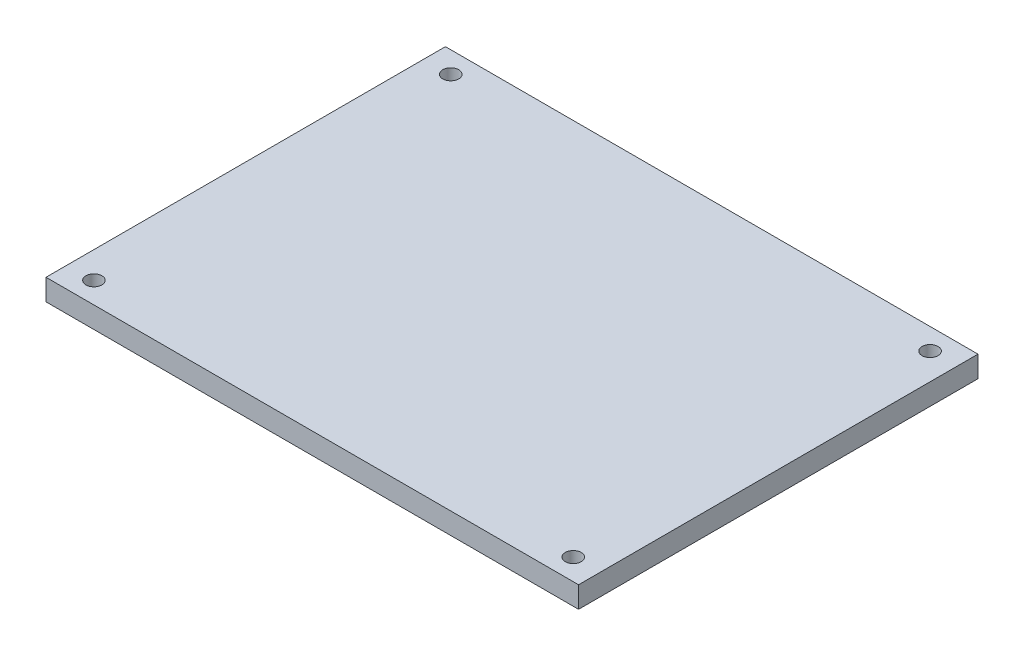
SolidWorks part; units mm, degrees
ref_plane "Front Plane" through (0, 0, 0) normal (0, 0, 1) x (1, 0, 0)
ref_plane "Top Plane" through (0, 0, 0) normal (0, 1, 0) x (1, 0, 0)
ref_plane "Right Plane" through (0, 0, 0) normal (1, 0, 0) x (0, 0, -1)
sketch "Sketch1" plane through (0, 0, 0) normal (0, 1, 0) x (1, 0, 0)
  line L0 (-50, 37.5) -> (50, 37.5)
  line L1 (-50, 37.5) -> (-50, -37.5)
  line L2 (-50, -37.5) -> (50, -37.5)
  line L3 (50, 37.5) -> (50, -37.5)
  circle A0 centre (-45, 33.5) radius 1.5
  circle A1 centre (-45, -33.5) radius 1.5
  circle A2 centre (45, 33.5) radius 1.5
  circle A3 centre (45, -33.5) radius 1.5
extrude "Boss-Extrude1" add sketch "Sketch1" along normal blind 4
